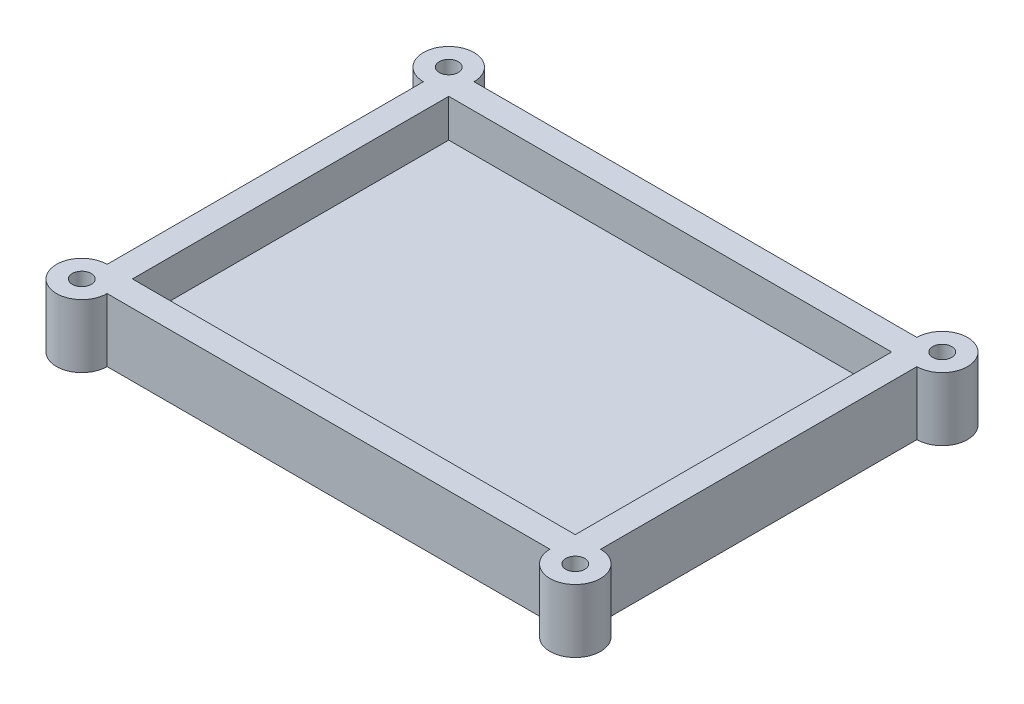
SolidWorks part; units mm, degrees
ref_plane "Front Plane" through (0, 0, 0) normal (0, 0, 1) x (1, 0, 0)
ref_plane "Top Plane" through (0, 0, 0) normal (0, 1, 0) x (1, 0, 0)
ref_plane "Right Plane" through (0, 0, 0) normal (1, 0, 0) x (0, 0, -1)
sketch "Sketch2" plane through (0, 0, 0) normal (0, 1, 0) x (1, 0, 0)
  line L1 (-195, 145) -> (195, 145)
  line L2 (-195, 145) -> (-195, -145)
  line L3 (-195, -145) -> (195, -145)
  line L4 (195, 145) -> (195, -145)
  line L5 (-195, 145) -> (195, -145) construction
  line L6 (-195, -145) -> (195, 145) construction
  point P0 (0, 0)
extrude "Boss-Extrude1" add sketch "Sketch2" along normal blind 50
shell "Shell1" thickness 20
sketch "Sketch3" plane through (0, 50, 0) normal (0, 1, 0) x (1, 0, 0)
  line L0 (0, 52.7661) -> (0, -57.18) construction
  line L1 (-56.1769, 0) -> (56.5781, 0) construction
  circle A0 centre (-195, 145) radius 20
  circle A1 centre (195, 145) radius 20
  circle A2 centre (195, -145) radius 20
  circle A3 centre (-195, -145) radius 20
extrude "Boss-Extrude2" add sketch "Sketch3" against normal blind 50
hole_wizard "Ø15.0 (15) Diameter Hole1" positions "Sketch4" profile "Sketch5" hole size "Ø15.0" standard "ANSI Metric"
sketch "Sketch4" plane through (0, 50, 0) normal (0, 1, 0) x (1, 0, 0)
  point P0 (-195, 145)
  point P3 (195, 145)
  point P6 (195, -145)
  point P9 (-195, -145)
sketch "Sketch5" plane through (-195, 50, -145) normal (1, 0, 0) x (0, 0, 1)
  line L0 (0, 0) -> (0, 24.5065)
  line L1 (0, 24.5065) -> (7.5, 20)
  line L2 (7.5, 20) -> (7.5, 0)
  line L5 (7.5, 0) -> (0, 0)
  line L10 (0, 24.5065) -> (-7.5, 20) construction
  line L11 (0, -6.35) -> (0, 107.95) construction
  dimension "Hole Dia." = 15
  dimension "Hole Depth" = 20
  dimension "Drill Angle" = 118
